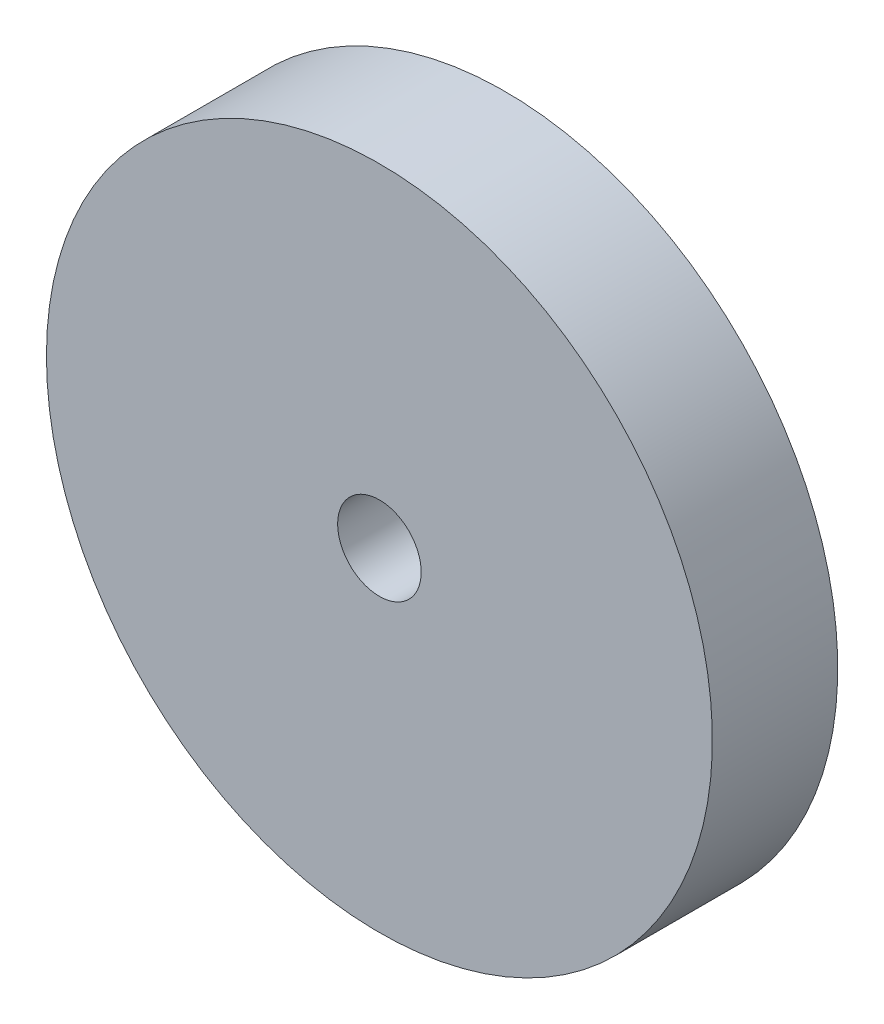
SolidWorks part; units mm, degrees
ref_plane "Front Plane" through (0, 0, 0) normal (0, 0, 1) x (1, 0, 0)
ref_plane "Top Plane" through (0, 0, 0) normal (0, 1, 0) x (1, 0, 0)
ref_plane "Right Plane" through (0, 0, 0) normal (1, 0, 0) x (0, 0, -1)
sketch "Sketch1" plane through (0, 0, 0) normal (0, 0, 1) x (1, 0, 0)
  circle A0 centre (0, 0) radius 202.4
  circle A1 centre (0, 0) radius 25.4
  dimension "D1" = 404.8
  dimension "D2" = 50.8
extrude "Boss-Extrude1" add sketch "Sketch1" along normal blind 76.2 contours A0 | A1
